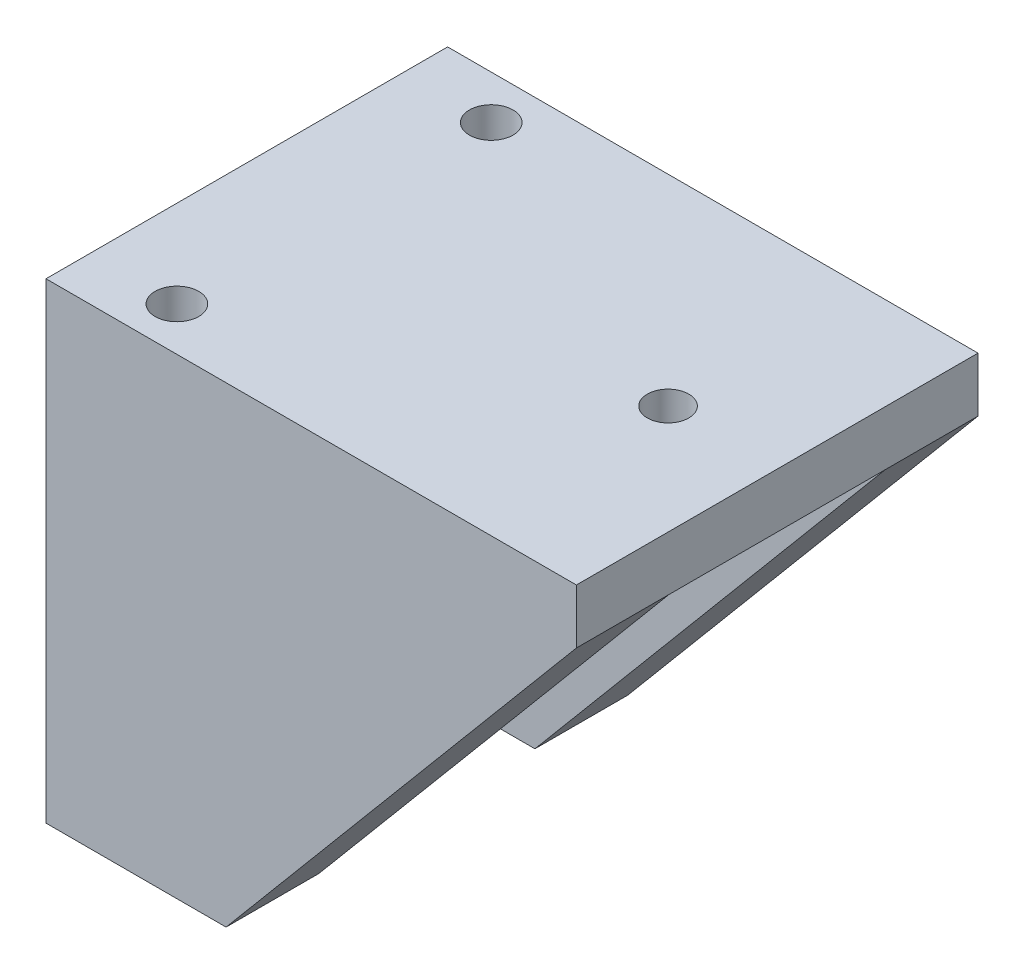
SolidWorks part; units mm, degrees
ref_plane "前基準面" through (0, 0, 0) normal (0, 0, 1) x (1, 0, 0)
ref_plane "上基準面" through (0, 0, 0) normal (0, 1, 0) x (1, 0, 0)
ref_plane "右基準面" through (0, 0, 0) normal (1, 0, 0) x (0, 0, -1)
sketch "草圖1" plane through (0, 0, 0) normal (0, 0, 1) x (1, 0, 0)
  line L0 (-40.6731, 29.7) -> (-40.6731, 2.8)
  line L1 (-0.0731, 34.7) -> (-0.0731, 29.7)
  line L2 (-48.6731, -8.5) -> (-40.6731, -8.5)
  line L3 (-40.6731, -8.5) -> (-40.6731, -3.2)
  line L4 (-48.6731, -8.5) -> (-48.6731, 0)
  line L6 (-48.6731, 0) -> (-40.6731, 0)
  line L7 (-48.6731, 2.8) -> (-40.6731, 2.8)
  line L8 (-40.6731, 0) -> (-40.6731, -3.2)
  line L11 (-48.6731, 2.8) -> (-48.6731, 34.7)
  line L12 (-41.6731, 34.7) -> (-48.6731, 34.7)
  line L17 (-41.6731, 34.7) -> (-0.0731, 34.7)
  line L19 (-40.6731, 29.7) -> (-0.0731, 29.7)
  dimension "D1" = 5
  dimension "D2" = 43.2
  dimension "D3" = 8
  dimension "D4" = 31.9
  dimension "D6" = 2.8
  dimension "D7" = 40.6
extrude "填料-伸長1" add sketch "草圖1" along normal blind 19.8
sketch "草圖2" plane through (-48.6731, 0, 0) normal (-1, 0, 0) x (0, 0, 1)
  line L0 (19.8, 0) -> (0, 0) construction
  line L1 (9.4, 0) -> (10.4, 0)
  line L2 (9.4, 0) -> (9.4, -0.8)
  line L3 (9.4, -0.8) -> (10.4, -0.8)
  line L4 (10.4, 0) -> (10.4, -0.8)
  dimension "D1" = 1
  dimension "D3" = 0.8
extrude "除料-伸長1" cut sketch "草圖2" against normal up to surface (8 mm away) up to face at (-40.6731, -4.25, 9.9)
sketch "草圖3" plane through (0, 0, 19.8) normal (0, 0, 1) x (1, 0, 0)
  line L0 (-48.6731, -8.5) -> (-32.1731, -8.5)
  line L1 (-0.0731, 34.7) -> (-0.0731, 29.7)
  line L2 (-0.0731, 29.7) -> (-32.1731, -8.5)
  line L4 (-0.0731, 34.7) -> (-48.6731, 34.7)
  line L6 (-48.6731, 34.7) -> (-48.6731, -8.5)
  dimension "D1" = 16.5
extrude "填料-伸長2" add sketch "草圖3" along normal blind 8.5
sketch "草圖4" plane through (0, 0, 0) normal (0, 0, -1) x (-1, 0, 0)
  line L0 (48.6731, -8.5) -> (48.6731, 34.7)
  line L1 (48.6731, 34.7) -> (0.0731, 34.7)
  line L2 (0.0731, 34.7) -> (0.0731, 29.7)
  line L3 (0.0731, 29.7) -> (32.1731, -8.5)
  line L4 (32.1731, -8.5) -> (48.6731, -8.5)
  dimension "D1" = 16.5
extrude "填料-伸長3" add sketch "草圖4" along normal blind 8.5
sketch "草圖5" plane through (0, 34.7, 0) normal (0, 1, 0) x (1, 0, 0)
  line L0 (-0.0731, -28.3) -> (-0.0731, 8.5) construction
  line L1 (-0.0731, -28.3) -> (-0.0731, 8.5) construction
  circle A0 centre (-10.0731, -9.9) radius 1.9
  point P6 (-0.0731, -9.9)
  dimension "D1" = 3.8
  dimension "D2" = 10
  dimension "D3" = 0
extrude "除料-伸長2" cut sketch "草圖5" against normal up to next
sketch "草圖8" plane through (-48.6731, 0, 0) normal (-1, 0, 0) x (0, 0, 1)
  line L0 (28.3, -8.5) -> (-8.5, -8.5) construction
  line L1 (0, 0) -> (19.8, 0)
  line L2 (0, 0) -> (0, -8.5)
  line L3 (0, -8.5) -> (19.8, -8.5)
  line L4 (19.8, 0) -> (19.8, -8.5)
  dimension "D1" = 19.8
extrude "除料-伸長5" cut sketch "草圖8" against normal up to surface (8 mm away) up to face at (-40.6731, 16.25, 9.9)
sketch "草圖9" plane through (0, 2.8, 0) normal (0, -1, 0) x (1, 0, 0)
  line L0 (-40.6731, 19.8) -> (-40.6731, 0) construction
  line L1 (-40.6731, 19.8) -> (-40.6731, 0) construction
  circle A0 centre (-45.2731, 14.9) radius 1.65
  circle A1 centre (-45.2731, 4.9) radius 1.65
  point P8 (-40.6731, 9.9)
  dimension "D1" = 4.6
  dimension "D2" = 3.3
  dimension "D3" = 3.3
  dimension "D4" = 4.6
  dimension "D5" = 5
  dimension "D6" = 10
extrude "填料-伸長4" add sketch "草圖9" along normal up to surface (11.3 mm away) up to face at (-40.4231, -8.5, 24.05)
sketch "草圖10" plane through (0, -8.5, 0) normal (0, -1, 0) x (-1, 0, 0)
  line L2 (40.6731, -19.8) -> (40.6731, 0) construction
  line L3 (48.6731, -28.3) -> (48.6731, -19.8) construction
  line L5 (48.6731, 0) -> (48.6731, 8.5) construction
  circle A0 centre (40.677, -24.3) radius 2
  circle A1 centre (40.6731, 4.4958) radius 2
  point P6 (48.6731, -24.05)
  point P11 (40.6731, -9.9)
  dimension "D1" = 4
  dimension "D2" = 4
  dimension "D3" = 8
  dimension "D4" = 8
  dimension "D5" = 14.4
  dimension "D6" = 28.7958
extrude "除料-伸長6" cut sketch "草圖10" against normal up to next
